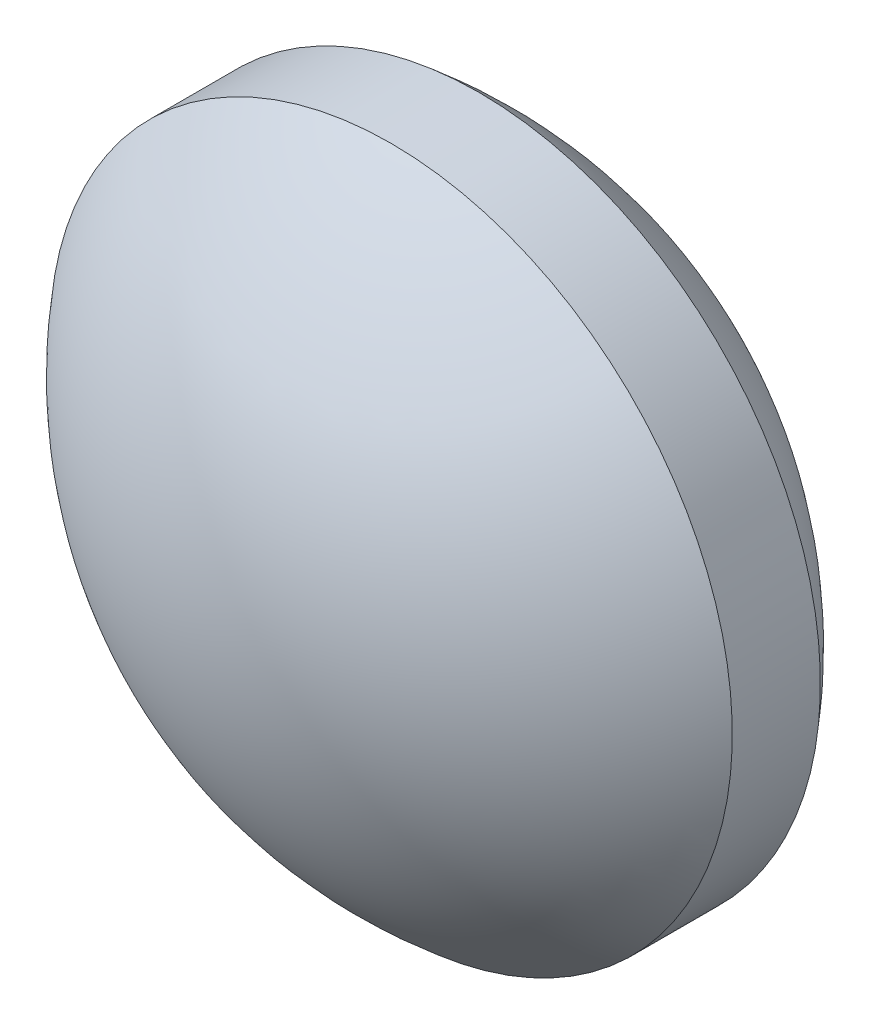
SolidWorks part; units mm, degrees
ref_plane "Front Plane" through (0, 0, 0) normal (0, 0, 1) x (1, 0, 0)
ref_plane "Top Plane" through (0, 0, 0) normal (0, 1, 0) x (1, 0, 0)
ref_plane "Right Plane" through (0, 0, 0) normal (1, 0, 0) x (0, 0, -1)
sketch "Sketch3" plane through (0, 0, 0) normal (1, 0, 0) x (0, 0, -1)
  line L0 (-2.3402, 0) -> (2.3402, 0)
  line L1 (0, 0) -> (0, 3.875)
  line L2 (-0.5, 3.875) -> (0.5, 3.875)
  line L3 (0, 0) -> (-2.6598, 0)
  arc A0 (2.3402, 0) -> (0.5, 3.875) centre (-2.6598, 0) ccw
  arc A1 (-2.3402, 0) -> (-0.5, 3.875) centre (2.6598, 0) cw
  dimension "D1" = 2.3402
  dimension "D2" = 3.875
  dimension "D3" = 0.5
  dimension "D4" = 2.6598
revolve "Revolve1" add sketch "Sketch3" angle 360 about L3
equation "\"T_edge\"= \"gloabl_scale\" * 1mm"
equation "\"R\"= \"gloabl_scale\" * 5mm"
equation "\"dT_c\"= \"R\" * ( 1 - sqr ( 1 - \"h\" ^ 2 / \"R\" ^ 2 ) )"
equation "\"h\"= \"gloabl_scale\" * 7.75 / 2mm"
equation "\"gloabl_scale\"= 1"
equation "\"x_sphere_origin\"= \"R\" - \"dT_c\" - \"T_edge\" / 2"
equation "\"T_c\"= \"T_edge\" + 2 * \"dT_c\""
equation "\"D1@Sketch3\"=\"T_c\" / 2"
equation "\"D2@Sketch3\"=\"h\""
equation "\"D3@Sketch3\"=\"T_edge\" / 2"
equation "\"D4@Sketch3\"=\"x_sphere_origin\""
